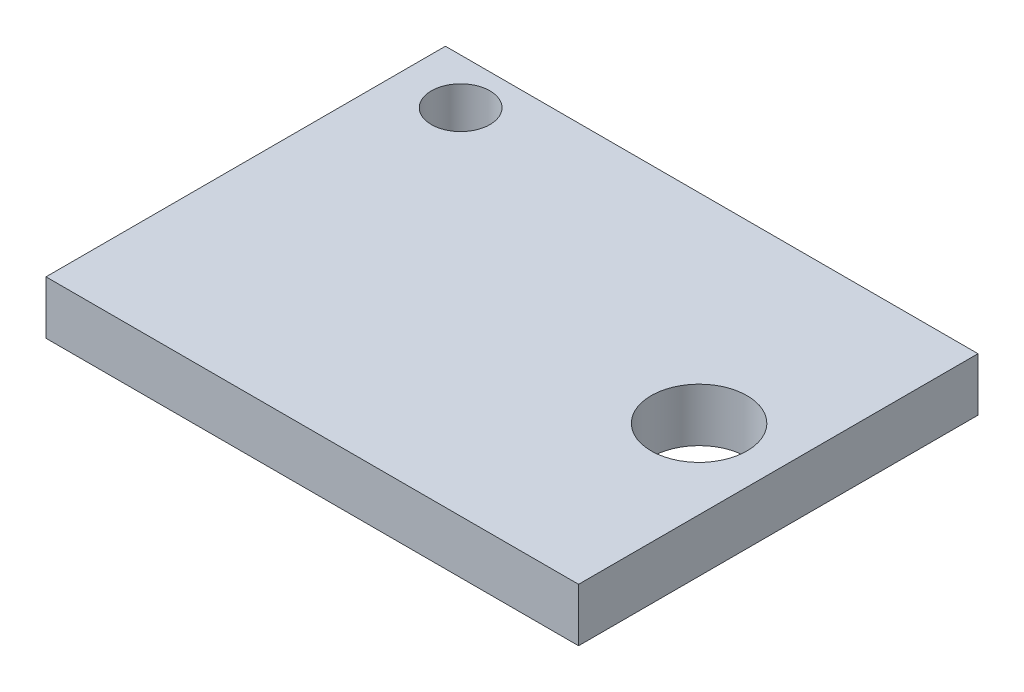
SolidWorks part; units mm, degrees
ref_plane "Front Plane" through (0, 0, 0) normal (0, 0, 1) x (1, 0, 0)
ref_plane "Top Plane" through (0, 0, 0) normal (0, 1, 0) x (1, 0, 0)
ref_plane "Right Plane" through (0, 0, 0) normal (1, 0, 0) x (0, 0, -1)
sketch "Sketch1" plane through (0, 0, 0) normal (0, 1, 0) x (1, 0, 0)
  line L1 (-50, 37.5) -> (50, 37.5)
  line L2 (-50, 37.5) -> (-50, -37.5)
  line L3 (-50, -37.5) -> (50, -37.5)
  line L4 (50, 37.5) -> (50, -37.5)
  line L5 (-50, 37.5) -> (50, -37.5) construction
  line L6 (-50, -37.5) -> (50, 37.5) construction
  circle A0 centre (35.1305, 0) radius 9
  circle A1 centre (-38.5714, 28.9286) radius 5.5
  point P0 (0, 0)
  dimension "D3" = 11
  dimension "D4" = 18
  dimension "D1" = 75
  dimension "D2" = 100
extrude "Boss-Extrude1" add sketch "Sketch1" along normal blind 10
